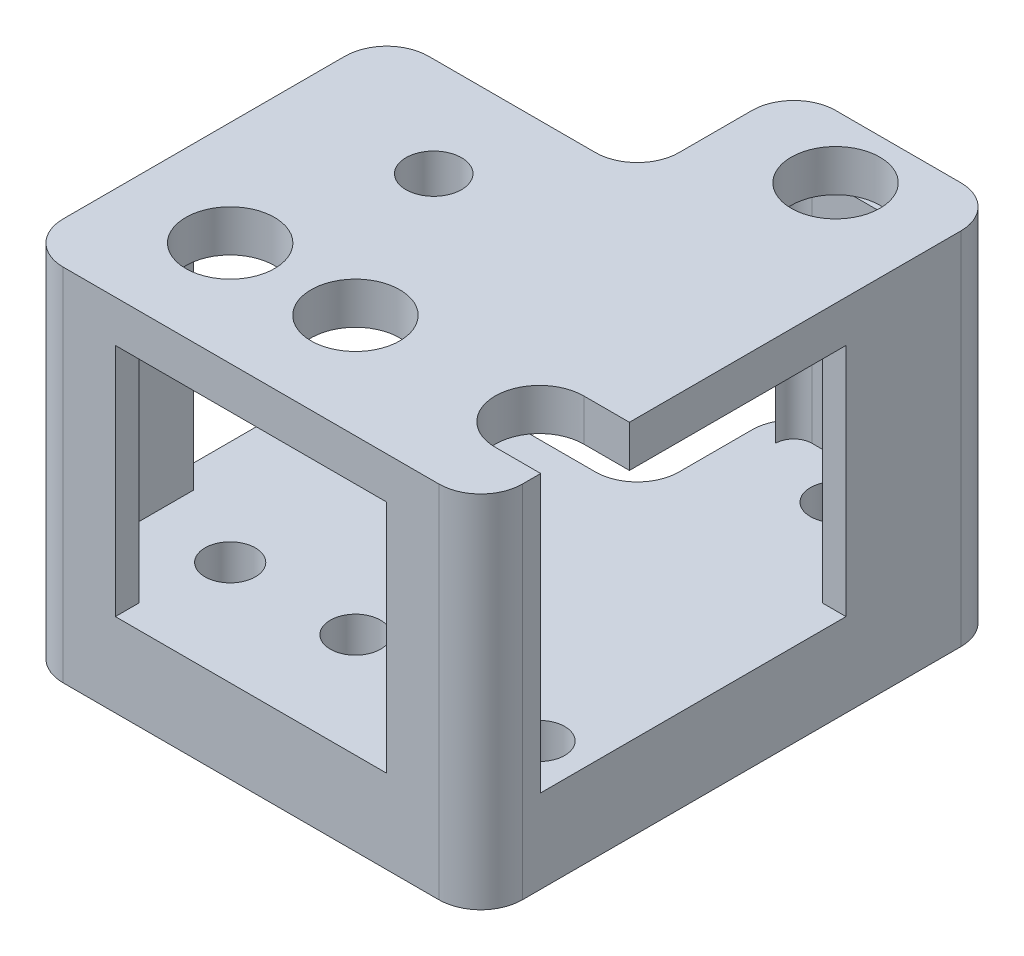
SolidWorks part; units mm, degrees
ref_plane "Front Plane" through (0, 0, 0) normal (0, 0, 1) x (1, 0, 0)
ref_plane "Top Plane" through (0, 0, 0) normal (0, 1, 0) x (1, 0, 0)
ref_plane "Right Plane" through (0, 0, 0) normal (1, 0, 0) x (0, 0, -1)
sketch "Sketch1" plane through (0, 0, 0) normal (0, 1, 0) x (1, 0, 0)
  line L0 (4, 0) -> (40, 0)
  line L1 (-55, 0) -> (55, 0) construction
  line L2 (44, 4) -> (44, 46)
  line L3 (40, 50) -> (28, 50)
  line L4 (24, 46) -> (24, 39)
  line L5 (20, 35) -> (4, 35)
  line L6 (0, -55) -> (0, 55) construction
  line L7 (0, 31) -> (0, 4)
  line L8 (24, 44) -> (44, 44) construction
  line L9 (42.05, 10) -> (44, 10) construction
  arc A0 (40, 0) -> (44, 4) centre (40, 4) ccw
  arc A1 (44, 46) -> (40, 50) centre (40, 46) ccw
  arc A2 (28, 50) -> (24, 46) centre (28, 46) ccw
  arc A3 (24, 39) -> (20, 35) centre (20, 39) cw
  arc A4 (4, 35) -> (0, 31) centre (4, 31) ccw
  arc A5 (0, 4) -> (4, 0) centre (4, 4) ccw
  circle A6 centre (34, 44) radius 2.4121
  circle A7 centre (14, 25.5) radius 2.6605
  circle A8 centre (10, 10) radius 2.4122
  circle A9 centre (22, 10) radius 2.4122
  circle A10 centre (39.6378, 10) radius 2.4122
  point P33 (34, 44)
  dimension "D4" = 4
  dimension "D6" = 4.8243
  dimension "D7" = 5.321
  dimension "D1" = 44
  dimension "D2" = 20
  dimension "D3" = 35
  dimension "D5" = 50
  dimension "D8" = 25.5
  dimension "D9" = 20
  dimension "D10" = 12
  dimension "D11" = 22
  dimension "D12" = 10
  dimension "D13" = 6
  dimension "D14" = 1.95
extrude "Boss-Extrude1" add sketch "Sketch1" along normal blind 8
sketch "Sketch2" plane through (0, 8, 0) normal (0, 1, 0) x (1, 0, 0)
  line L0 (4, 35) -> (20, 35)
  line L1 (24, 39) -> (24, 46)
  line L2 (28, 50) -> (40, 50)
  line L3 (44, 46) -> (44, 4)
  line L4 (-55, 0) -> (55, 0) construction
  line L5 (40, 0) -> (4, 0)
  line L6 (0, -55) -> (0, 55) construction
  line L7 (0, 4) -> (0, 31)
  line L9 (41.75, 46) -> (41.75, 4)
  line L10 (40, 2.25) -> (4, 2.25)
  line L11 (2.25, 4) -> (2.25, 31)
  line L12 (4, 32.75) -> (20, 32.75)
  line L13 (26.25, 39) -> (26.25, 46)
  line L14 (40, 47.75) -> (28, 47.75)
  arc A0 (20, 35) -> (24, 39) centre (20, 39) ccw
  arc A1 (24, 46) -> (28, 50) centre (28, 46) cw
  arc A2 (28, 50) -> (24, 46) centre (28, 46) ccw construction
  arc A3 (40, 50) -> (44, 46) centre (40, 46) cw
  arc A4 (44, 4) -> (40, 0) centre (40, 4) cw
  arc A5 (4, 0) -> (0, 4) centre (4, 4) cw
  arc A6 (4, 35) -> (0, 31) centre (4, 31) ccw construction
  arc A7 (0, 4) -> (4, 0) centre (4, 4) ccw construction
  arc A8 (40, 47.75) -> (41.75, 46) centre (40, 46) cw
  arc A9 (41.75, 4) -> (40, 2.25) centre (40, 4) cw
  arc A10 (4, 2.25) -> (2.25, 4) centre (4, 4) cw
  arc A11 (2.25, 31) -> (4, 32.75) centre (4, 31) cw
  arc A12 (20, 32.75) -> (26.25, 39) centre (20, 39) ccw
  arc A13 (28, 47.75) -> (26.25, 46) centre (28, 46) ccw
  arc A14 (4, 35) -> (0, 31) centre (4, 31) ccw
  dimension "D1" = 2.25
extrude "Boss-Extrude2" add sketch "Sketch2" along normal blind 22.5
sketch "Sketch3" plane through (0, 30.5, 0) normal (0, 1, 0) x (1, 0, 0)
  line L1 (40, 50) -> (28, 50) construction
  line L2 (26.25, 50) -> (14, 50)
  line L3 (14, 14.5) -> (0, 14.5)
  line L4 (14, 50) -> (14, 36.5)
  line L5 (3, 25.5) -> (0, 25.5)
  line L6 (0, -4.4) -> (0, 4.4) construction
  line L7 (0, 25.5) -> (0, 14.5)
  line L9 (26.25, 25.5) -> (26.25, 50)
  line L10 (26.25, 46) -> (26.25, 39) construction
  line L11 (25, 25.5) -> (26.25, 25.5)
  arc A0 (14, 14.5) -> (25, 25.5) centre (14, 25.5) ccw
  circle A1 centre (14, 25.5) radius 11 construction
  arc A2 (14, 36.5) -> (3, 25.5) centre (14, 25.5) ccw
  dimension "D1" = 22
  dimension "D2" = 22
extrude "Cut-Extrude1" cut sketch "Sketch3" against normal up to surface (22.5 mm away) up to face at (10, 8, -7.5878)
sketch "Sketch4" plane through (0, 30.5, 0) normal (0, 1, 0) x (1, 0, 0)
  line L0 (28, 50) -> (40, 50)
  line L1 (44, 46) -> (44, 4)
  line L2 (-4.4, 0) -> (4.4, 0) construction
  line L3 (40, 0) -> (4, 0)
  line L4 (0, -4.4) -> (0, 4.4) construction
  line L5 (0, 4) -> (0, 31)
  line L6 (4, 35) -> (20, 35)
  line L7 (24, 39) -> (24, 46)
  arc A0 (40, 50) -> (44, 46) centre (40, 46) cw
  arc A1 (44, 4) -> (40, 0) centre (40, 4) cw
  arc A2 (0, 4) -> (4, 0) centre (4, 4) ccw construction
  arc A3 (4, 0) -> (0, 4) centre (4, 4) cw
  arc A4 (4, 35) -> (0, 31) centre (4, 31) ccw construction
  arc A5 (0, 31) -> (4, 35) centre (4, 31) cw
  arc A6 (20, 35) -> (24, 39) centre (20, 39) ccw
  arc A7 (24, 46) -> (28, 50) centre (28, 46) cw
  circle A8 centre (34, 44) radius 4.25
  circle A9 centre (14, 25.5) radius 2.6605
  circle A10 centre (22, 10) radius 4.25
  circle A11 centre (10, 10) radius 4.25
  circle A12 centre (14, 25.5) radius 2.6605 construction
  circle A13 centre (39.6378, 10) radius 4.25
  dimension "D1" = 8.5
extrude "Boss-Extrude3" add sketch "Sketch4" along normal blind 4
sketch "Sketch5" plane through (0, 34.5, 0) normal (0, 1, 0) x (1, 0, 0)
  line L0 (39.6378, 14.25) -> (44, 14.25)
  line L1 (44, 4) -> (44, 46) construction
  line L2 (44, 14.25) -> (44, 5.75)
  line L3 (44, 5.75) -> (39.6378, 5.75)
  arc A0 (39.6378, 14.25) -> (39.6378, 5.75) centre (39.6378, 10) ccw
  circle A1 centre (39.6378, 10) radius 4.25 construction
  arc A2 (41.75, 6.312) -> (41.75, 13.688) centre (39.6378, 10) ccw construction
extrude "Cut-Extrude2" cut sketch "Sketch5" against normal up to surface (26.5 mm away) up to face at (19.1826, 8, -27.3211)
sketch "Sketch6" plane through (0, 8, 0) normal (0, 1, 0) x (1, 0, 0)
  circle A0 centre (14, 25.5) radius 10
  circle A1 centre (14, 25.5) radius 2.6605 construction
  dimension "D1" = 20
extrude "Boss-Extrude4" add sketch "Sketch6" along normal blind 6
sketch "Sketch7" plane through (0, 0, 0) normal (0, -1, 0) x (1, 0, 0)
  line L0 (4, -35) -> (20, -35)
  line L1 (20, -35) -> (20, -40)
  line L2 (20, -40) -> (4, -40)
  line L3 (4, -40) -> (4, -35)
  circle A0 centre (14, -25.5) radius 2.6605
  circle A1 centre (14, -25.5) radius 2.6605 construction
  dimension "D1" = 5
extrude "Cut-Extrude3" cut sketch "Sketch7" against normal through all
sketch "Sketch8" plane through (44, 0, 0) normal (1, 0, 0) x (0, 0, -1)
  line L0 (14.25, 8) -> (14.25, 34.5) construction
  line L1 (14.25, 30.5) -> (35, 30.5)
  line L2 (14.25, 30.5) -> (14.25, 8)
  line L3 (14.25, 8) -> (35, 8)
  line L4 (35, 30.5) -> (35, 8)
  line L5 (5.75, 30.5) -> (14.25, 30.5) construction
  line L6 (14.25, 8) -> (5.75, 8) construction
  line L8 (35, 30.5) -> (35, 8) construction
extrude "Cut-Extrude4" cut sketch "Sketch8" against normal through all
sketch "Sketch9" plane through (0, 0, 0) normal (0, 0, 1) x (1, 0, 0)
  line L1 (9, 30.5) -> (35, 30.5)
  line L2 (9, 30.5) -> (9, 8)
  line L3 (9, 8) -> (35, 8)
  line L4 (35, 30.5) -> (35, 8)
  line L5 (40, 8) -> (28, 8) construction
  line L6 (39.6378, 30.5) -> (44, 30.5) construction
  line L7 (4, 34.5) -> (4, 0) construction
  line L8 (40, 34.5) -> (40, 0) construction
  dimension "D1" = 5
  dimension "D2" = 5
extrude "Cut-Extrude5" cut sketch "Sketch9" against normal up to surface (2.25 mm away) up to face at (22, 19.25, -2.25)
